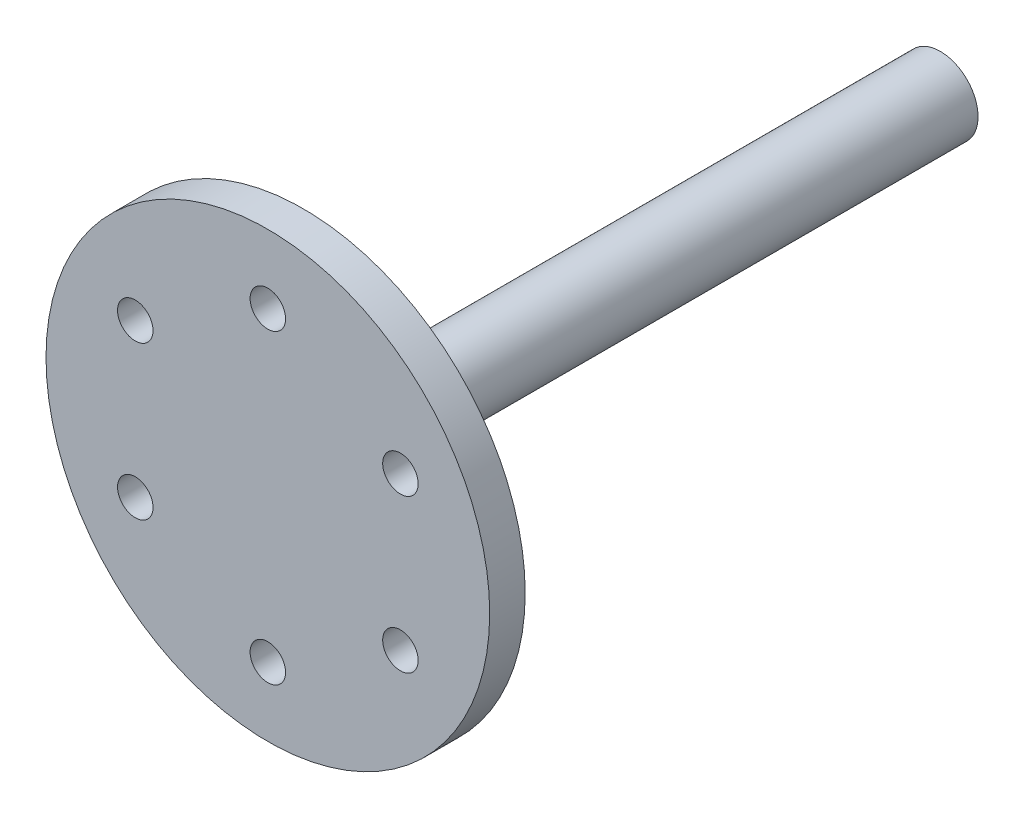
SolidWorks part; units mm, degrees
ref_plane "前视基准面" through (0, 0, 0) normal (0, 0, 1) x (1, 0, 0)
ref_plane "上视基准面" through (0, 0, 0) normal (0, 1, 0) x (1, 0, 0)
ref_plane "右视基准面" through (0, 0, 0) normal (1, 0, 0) x (0, 0, -1)
sketch "草图1" plane through (0, 0, 0) normal (0, 0, 1) x (1, 0, 0)
  circle A0 centre (0, 0) radius 25
  dimension "D1" = 50
extrude "凸台-拉伸1" add sketch "草图1" along normal blind 4
sketch "草图2" plane through (0, 0, 0) normal (0, 0, -1) x (-1, 0, 0)
  circle A0 centre (0.2169, 0) radius 4.25
  dimension "D1" = 8.5
extrude "凸台-拉伸2" add sketch "草图2" along normal blind 72
sketch "草图3" plane through (0, 0, 0) normal (0, 0, -1) x (-1, 0, 0)
  circle A1 centre (0, 17.25) radius 2
  circle A2 centre (14.9389, 8.625) radius 2
  circle A3 centre (14.9389, -8.625) radius 2
  circle A4 centre (0, -17.25) radius 2
  circle A5 centre (-14.9389, -8.625) radius 2
  circle A6 centre (-14.9389, 8.625) radius 2
  point P18 (0, 0)
  dimension "D2" = 4
  dimension "D3" = 6
extrude "切除-拉伸1" cut sketch "草图3" against normal blind 100
